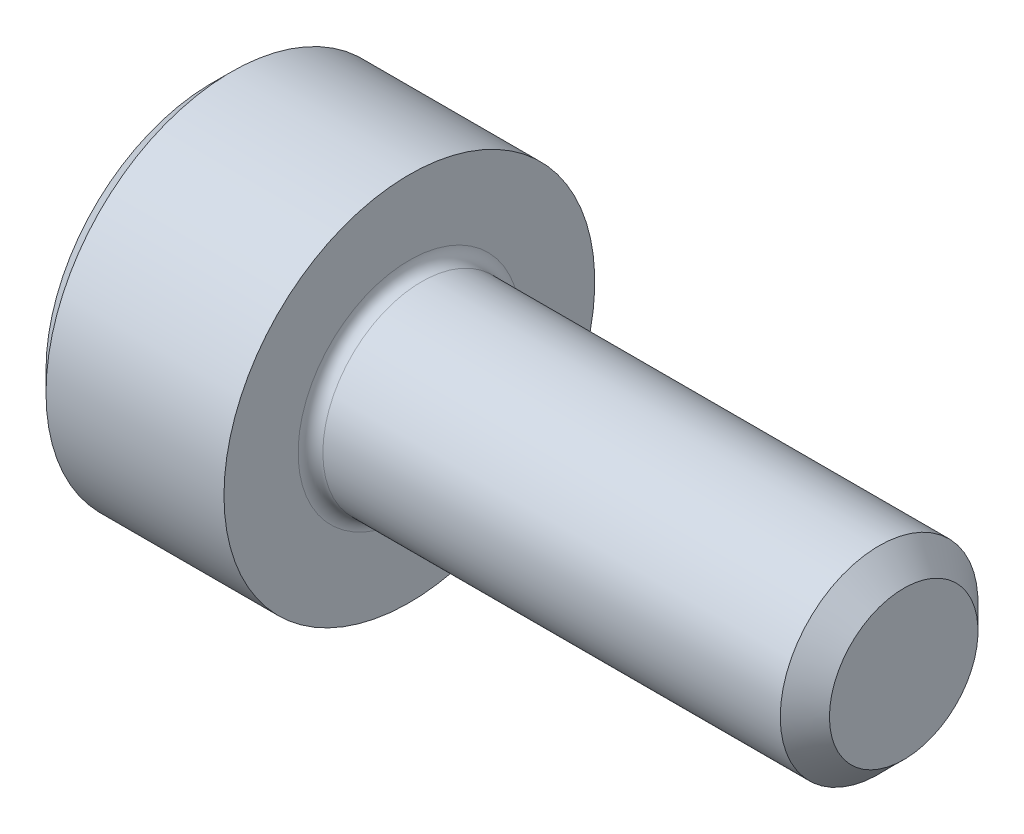
SolidWorks part; units mm, degrees
revolve "Base-Revolve" add sketch "BodySke"
sketch "BodySke" plane through (0, 0, 0) normal (0, 0, 1) x (1, 0, 0)
  line L0 (0, 0) -> (0, 1.34)
  line L1 (0.16, 1.5) -> (1.6, 1.5)
  line L2 (1.6, 1.5) -> (1.6, 0.8)
  line L3 (1.6, 0.8) -> (5.401, 0.8)
  line L4 (5.6, 0.601) -> (5.6, 0)
  line L5 (5.6, 0) -> (0, 0)
  line L6 (-31.75, 0) -> (127, 0) construction
  line L7 (0, 1.34) -> (0.16, 1.5)
  line L8 (5.6, 0.601) -> (5.401, 0.8)
  line L9 (0, -1.34) -> (0.16, -1.5) construction
  line L10 (5.6, -0.601) -> (5.401, -0.8) construction
  line L11 (1.95, 9.525) -> (1.95, 3.175) construction
  line L12 (1.6, 9.525) -> (1.6, 3.175) construction
  line L13 (-44.4, 9.525) -> (-44.4, 3.175) construction
  dimension "Diameter" = 1.6
  dimension "Head_ht" = 1.6
  dimension "Length" = 4
  dimension "Body_ch_ang" = 45
  dimension "Head_dia" = 3
  dimension "Head_ch_ang" = 45
  dimension "Minor_dia" = 1.202
  dimension "Advance" = 0.35
  dimension "Thread_nom" = 4
  dimension "Thread_length" = 50
  dimension "Head_ch_ht" = 0.16
cosmetic thread "ThreadCosmetic" [suppressed]
fillet "Fillet1" radius 0.1 1 edges at (1.6, 0, 0.8)
ref_plane "Plane1" through (0, 0, 0) normal (0, 0, 1) x (1, 0, 0)
ref_plane "Plane2" through (0, 0, 0) normal (0, 1, 0) x (1, 0, 0)
ref_plane "Plane3" through (0, 0, 0) normal (1, 0, 0) x (0, 0, -1)
sketch "Sketch2" plane through (0, 0, 0) normal (0, 0, 1) x (1, 0, 0)
  line L0 (0, 0.7725) -> (0.7, 0.7725)
  line L1 (0.7, 0.7725) -> (1.146, 0)
  line L2 (-31.75, 0) -> (127, 0) construction
  line L3 (1.146, 0) -> (0, 0)
  line L4 (0, 0) -> (0, 0.7725)
  line L5 (0, 1.34) -> (0, -1.34) construction
  line L6 (0, 0) -> (47.625, 0) construction
  line L7 (1.6, -1.5) -> (1.6, 1.5) construction
  dimension "D1" = 0.7725
  dimension "D2" = 60
revolve "Hex-PreBroach" cut sketch "Sketch2" angle 360 about L6
sketch "Sketch3" plane through (0, 0, 0) normal (-1, 0, 0) x (0, 0.5, 0.866)
  line L0 (0.446, 0.7725) -> (-0.446, 0.7725)
  line L1 (-0.446, 0.7725) -> (-0.892, 0)
  line L2 (0.446, 0.7725) -> (0.892, 0)
  line L3 (0.446, -0.7725) -> (0.892, 0)
  line L4 (0.446, -0.7725) -> (-0.446, -0.7725)
  line L5 (-0.446, -0.7725) -> (-0.892, 0)
  dimension "D1" = 0.7725
  dimension "D2" = 0.7725
  dimension "Hex_size" = 1.545
extrude "Hex" cut sketch "Sketch3" against normal blind 0.7
sketch "Sketch4" plane through (0, 0, 0) normal (-1, 0, 0) x (0, 0, 1)
  line L0 (0, 0) -> (0.9398, 0)
  line L1 (0, 0) -> (6.1484, 3.5498) construction
  line L2 (0, 0) -> (0.4699, 0.8139)
  line L3 (0.7832, 0.2175) -> (0.8962, 0.2828)
  line L4 (0.58, 0.5695) -> (0.693, 0.6348)
  arc A0 (0.7832, 0.2175) -> (0.58, 0.5695) centre (0, 0) ccw
  arc A1 (0.9398, 0) -> (0.8962, 0.2828) centre (0, 0) ccw
  arc A2 (0.4699, 0.8139) -> (0.693, 0.6348) centre (0, 0) cw
  dimension "D1" = 30
  dimension "D2" = 60
  dimension "Spline_p_dim" = 0.4064
  dimension "D3" = 0.2032
extrude "Spline" [suppressed] cut sketch "Sketch4" against normal blind 0.7
pattern_circular "CirPattern1" [suppressed] count 6 every 60
sketch "Sketch5" plane through (0, 0, 0) normal (0, 0, 1) x (1, 0, 0)
  line L0 (-31.75, 0) -> (127, 0) construction
  line L2 (0, 1.34) -> (0, -1.34) construction
  circle A0 centre (0.1, 0) radius 0.005
  dimension "Drilled_hole_dia" = 0.01
  dimension "Drilled_hole_loc" = 0.1
extrude "Hole" [suppressed] cut sketch "Sketch5" against normal through all and the other way through all
pattern_circular "Drilled-4" [suppressed] count 2 every 60
pattern_circular "Drilled-6" [suppressed] count 3 every 60
sketch "ThdSchSke" plane through (0, 0, 0) normal (0, 0, 1) x (1, 0, 0)
  line L0 (1.95, -0.601) -> (1.8107, -0.8)
  line L1 (1.95, -0.601) -> (2.0893, -0.8)
  line L2 (2.0893, -0.8) -> (2.0893, -1)
  line L3 (-3.175, 0) -> (5.1513, 0) construction
  line L5 (2.0893, -1) -> (1.8107, -1)
  line L6 (1.8107, -1) -> (1.8107, -0.8)
  line L7 (0, 1.34) -> (0, -1.34) construction
  dimension "Thread_minor" = 1.202
  dimension "Diameter" = 1.6
  dimension "Start" = 1.95
revolve "ThreadSchematic" [suppressed] cut sketch "ThdSchSke" angle 360 about L3
pattern_linear "ThdSchPat" [suppressed]
equation "\"D2@Sketch3\" = \"Hex_size@Sketch3\" / 2"
equation "\"D1@Sketch3\" = \"Hex_size@Sketch3\" / 2"
equation "\"D1@Sketch2\" = \"Hex_size@Sketch3\" / 2"
equation "\"D3@Sketch4\" = \"Spline_p_dim@Sketch4\" / 2"
equation "\"Thread_minor@ThreadCosmetic\"  =  \"Minor_dia@BodySke\""
equation "\"D2@CirPattern1\" = 360 / \"Num_teeth@CirPattern1\""
equation "\"Wall_thickness@Sketch2\" = \"Head_ht@BodySke\" - \"Key_eng@Hex\""
equation "\"Thread_length@ThreadCosmetic\" = ((sgn( (\"Length@BodySke\" - \"Advance@BodySke\" ) - \"Thread_nom@BodySke\" )-1)*( (\"Length@BodySke\" - \"Advance@BodySke\" ) - \"Thread_nom@BodySke\" ))/-2+ \"Thread_nom@BodySke\""
equation "\"Thread_minor@ThdSchSke\" = \"Minor_dia@BodySke\""
equation "\"Diameter@ThdSchSke\" = \"Diameter@BodySke\""
equation "\"Overcut@ThdSchSke\" = \"Diameter@BodySke\" * 1.25"
equation "\"Start@ThdSchSke\" = \"Head_ht@BodySke\" + \"Length@BodySke\" - \"Thread_length@ThreadCosmetic\"  '---Non-countersunk---"
equation "\"Num_threads@ThdSchPat\" = int( \"Thread_length@ThreadCosmetic\" / \"Advance@BodySke\" + 0.999 )  + 1"
equation "\"Advance@ThdSchPat\" = \"Thread_length@ThreadCosmetic\" /  (\"Num_threads@ThdSchPat\" - 1) 'relax it"
equation "\"Num_threads@ThdSchPat\" = \"Num_threads@ThdSchPat\" - sgn( \"Num_threads@ThdSchPat\" - 1) '---chamfered tips only---"
